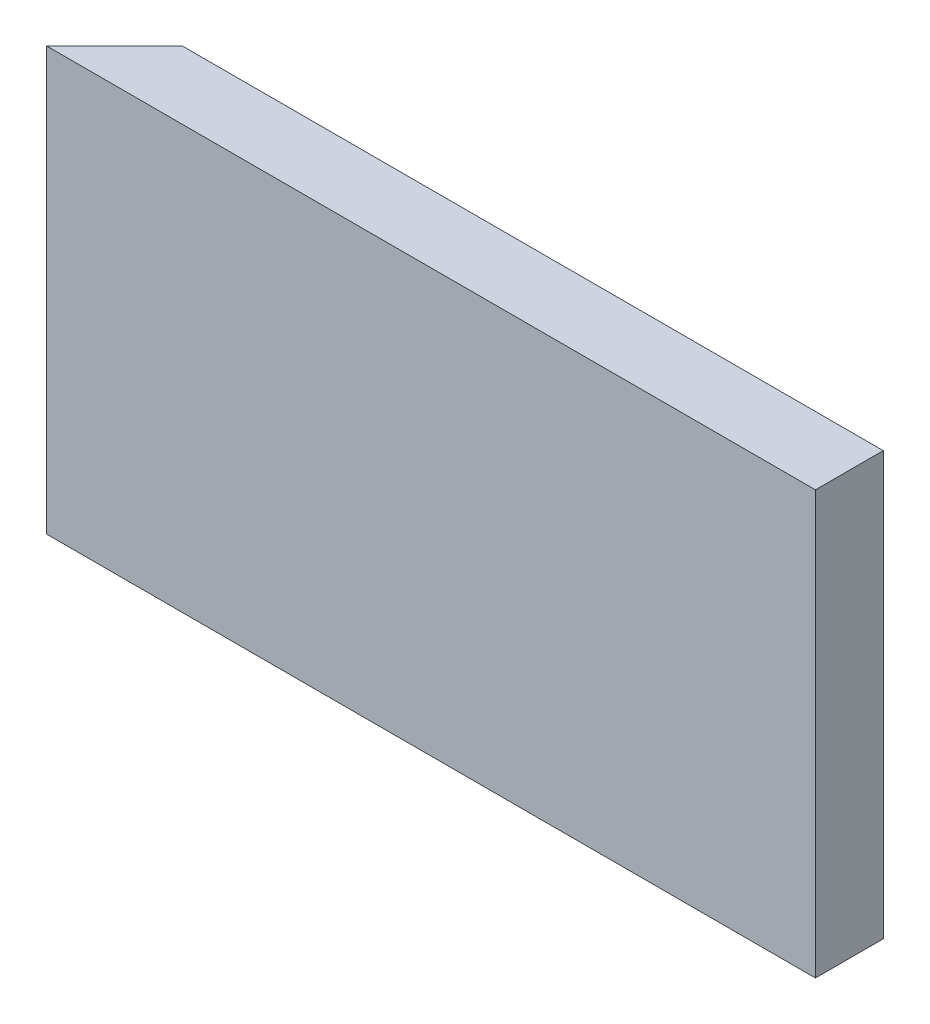
SolidWorks part; units mm, degrees
ref_plane "Front Plane" through (0, 0, 0) normal (0, 0, 1) x (1, 0, 0)
ref_plane "Top Plane" through (0, 0, 0) normal (0, 1, 0) x (1, 0, 0)
ref_plane "Right Plane" through (0, 0, 0) normal (1, 0, 0) x (0, 0, -1)
sketch "Sketch1" plane through (0, 0, 0) normal (1, 0, 0) x (0, 0, -1)
  line L1 (0, 0) -> (19.05, 0)
  line L2 (0, 0) -> (0, 118.745)
  line L3 (0, 118.745) -> (19.05, 118.745)
  line L4 (19.05, 0) -> (19.05, 118.745)
extrude "Boss-Extrude1" add sketch "Sketch1" along normal blind 215.9
sketch "Sketch2" plane through (0, 0, 0) normal (0, 1, 0) x (1, 0, 0)
  line L0 (0, 0) -> (19.05, 19.05)
  line L1 (215.9, 19.05) -> (0, 19.05) construction
  line L2 (19.05, 19.05) -> (0, 19.05)
  line L3 (0, 19.05) -> (0, 0)
extrude "Cut-Extrude5" cut sketch "Sketch2" along normal blind 215.9
